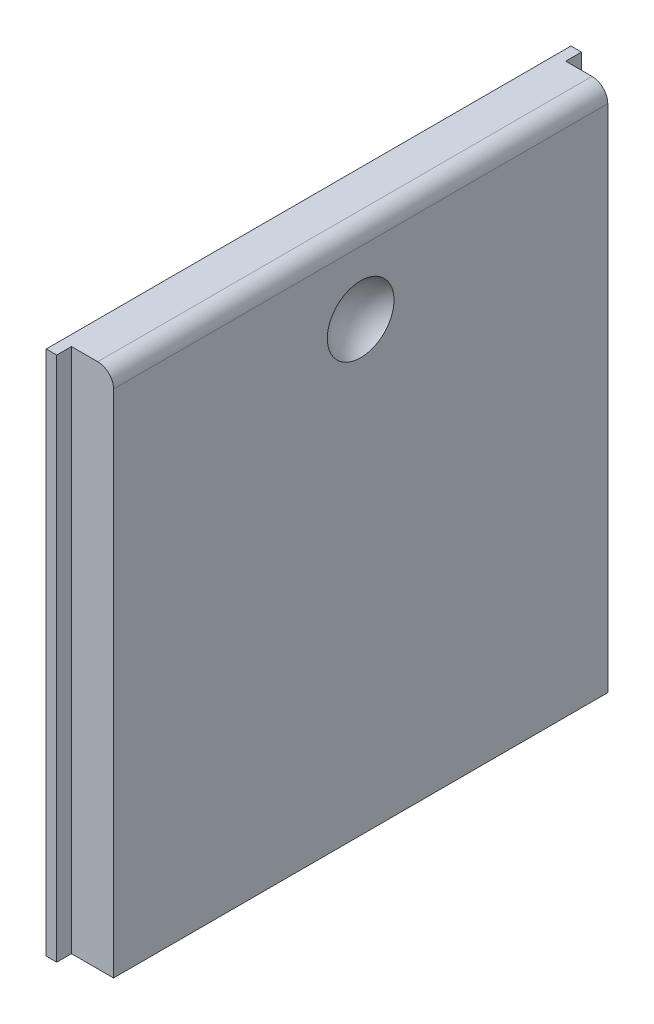
SolidWorks part; units mm, degrees
material "ABS"
ref_plane "Front Plane" through (0, 0, 0) normal (0, 0, 1) x (1, 0, 0)
ref_plane "Top Plane" through (0, 0, 0) normal (0, 1, 0) x (1, 0, 0)
ref_plane "Right Plane" through (0, 0, 0) normal (1, 0, 0) x (0, 0, -1)
sketch "Sketch2" plane through (0, 0, 0) normal (0, 1, 0) x (1, 0, 0)
  line L1 (0, -47) -> (-8, -47)
  line L2 (0, -47) -> (0, 47)
  line L3 (0, 47) -> (-8, 47)
  line L4 (-10, -47.4) -> (-10, 47.6)
  line L6 (-10, 47.6) -> (-10, 50)
  line L7 (-10, 50) -> (-8, 50)
  line L8 (-8, 47) -> (-8, 50)
  line L10 (-10, -47.4) -> (-10, -49.8)
  line L11 (-10, -49.8) -> (-8, -49.8)
  line L12 (-8, -47) -> (-8, -49.8)
  dimension "D1" = 94
  dimension "D2" = 2
  dimension "D3" = 2
  dimension "D4" = 2.4
  dimension "D5" = 2.4
  dimension "D6" = 10
  dimension "D7" = 95
  dimension "D8" = 3
extrude "Boss-Extrude1" add sketch "Sketch2" along normal blind 100
fillet "Fillet2" radius 3 1 edges at (0, 100, 0)
sketch "Sketch3" plane through (0, 0, 0) normal (0, 0, 1) x (1, 0, 0)
  line L1 (-8, 100) -> (-3, 100) construction
  line L2 (-10, 100) -> (-10, 0) construction
  line L3 (-3.5, 85) -> (11.5, 85) construction
  line L4 (-3.5, 85) -> (11.5, 85)
  arc A0 (11.5, 85) -> (-3.5, 85) centre (4, 85) ccw
  dimension "D1" = 15
  dimension "D2" = 15
  dimension "D3" = 14
revolve "Cut-Revolve1" cut sketch "Sketch3" angle 360 about L3
